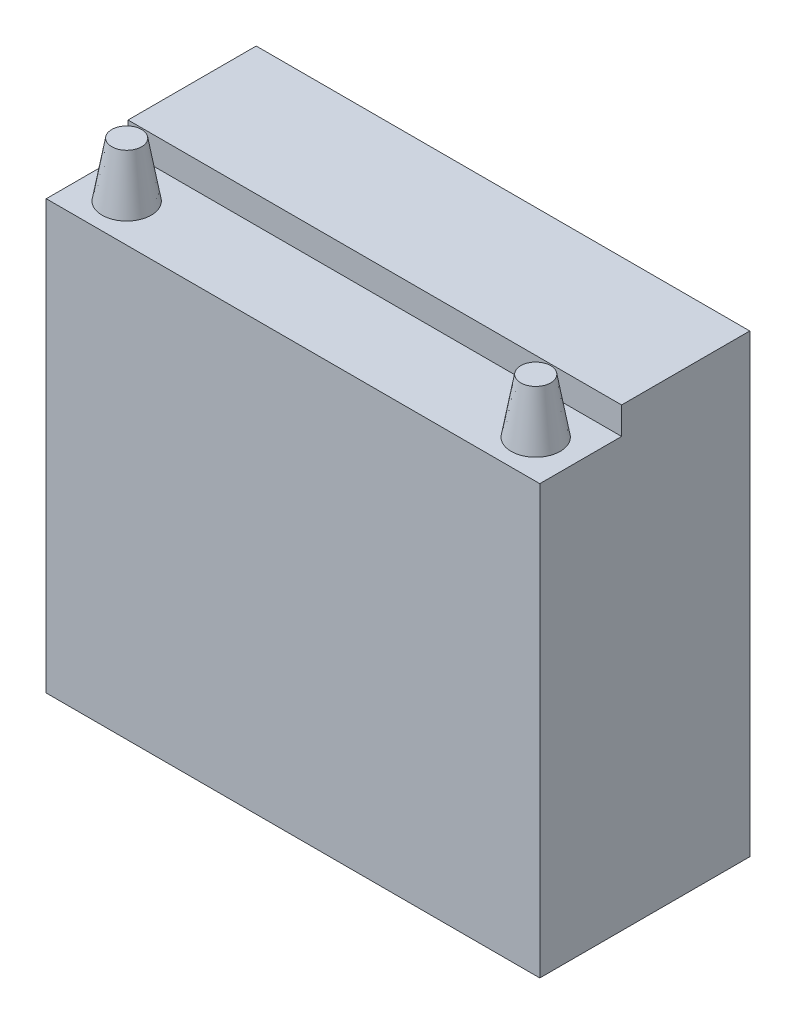
SolidWorks part; units mm, degrees
ref_plane "Plano frontal" through (0, 0, 0) normal (0, 0, 1) x (1, 0, 0)
ref_plane "Plano superior" through (0, 0, 0) normal (0, 1, 0) x (1, 0, 0)
ref_plane "Plano direito" through (0, 0, 0) normal (1, 0, 0) x (0, 0, -1)
ref_plane "Plano1" through (0, 0, -45.1693) normal (0, 0, -1) x (-1, 0, 0)
sketch "Esboço1" plane through (0, 0, -45.1693) normal (0, 0, -1) x (-1, 0, 0)
  line L0 (77, 0) -> (77, 167)
  line L1 (77, 167) -> (-104, 167)
  line L2 (-104, 167) -> (-104, 0)
  line L3 (-104, 0) -> (77, 0)
extrude "Ressalto-extrusão1" add sketch "Esboço1" against normal blind 77
sketch "Esboço2" plane through (-77, 0, 0) normal (-1, 0, 0) x (0, 0, 1)
  line L0 (1.8307, 167) -> (1.8307, 157)
  line L1 (1.8307, 157) -> (31.8307, 157)
  line L2 (31.8307, 157) -> (31.8307, 167)
  line L3 (31.8307, 167) -> (1.8307, 167)
extrude "Corte-extrusão1" cut sketch "Esboço2" against normal through all
ref_plane "Plano2" through (0, 0, 17.8307) normal (0, 0, -1) x (-1, 0, 0)
sketch "Esboço3" plane through (0, 0, 17.8307) normal (0, 0, -1) x (-1, 0, 0)
  line L0 (-97.5, 157) -> (-88.5, 157)
  line L1 (-88.5, 157) -> (-88.5, 177)
  line L2 (-88.5, 177) -> (-93.9735, 177)
  line L3 (-93.9735, 177) -> (-97.5, 157)
  line L4 (-88.5, 157) -> (-88.5, 177) construction
revolve "Revolução1" add sketch "Esboço3" angle 360 about L4
sketch "Esboço4" plane through (0, 0, 17.8307) normal (0, 0, -1) x (-1, 0, 0)
  line L0 (52.5, 157) -> (61.5, 157)
  line L1 (61.5, 157) -> (61.5, 177)
  line L2 (61.5, 177) -> (56.0265, 177)
  line L3 (56.0265, 177) -> (52.5, 157)
  line L4 (61.5, 157) -> (61.5, 177) construction
revolve "Revolução2" add sketch "Esboço4" angle 360 about L4
